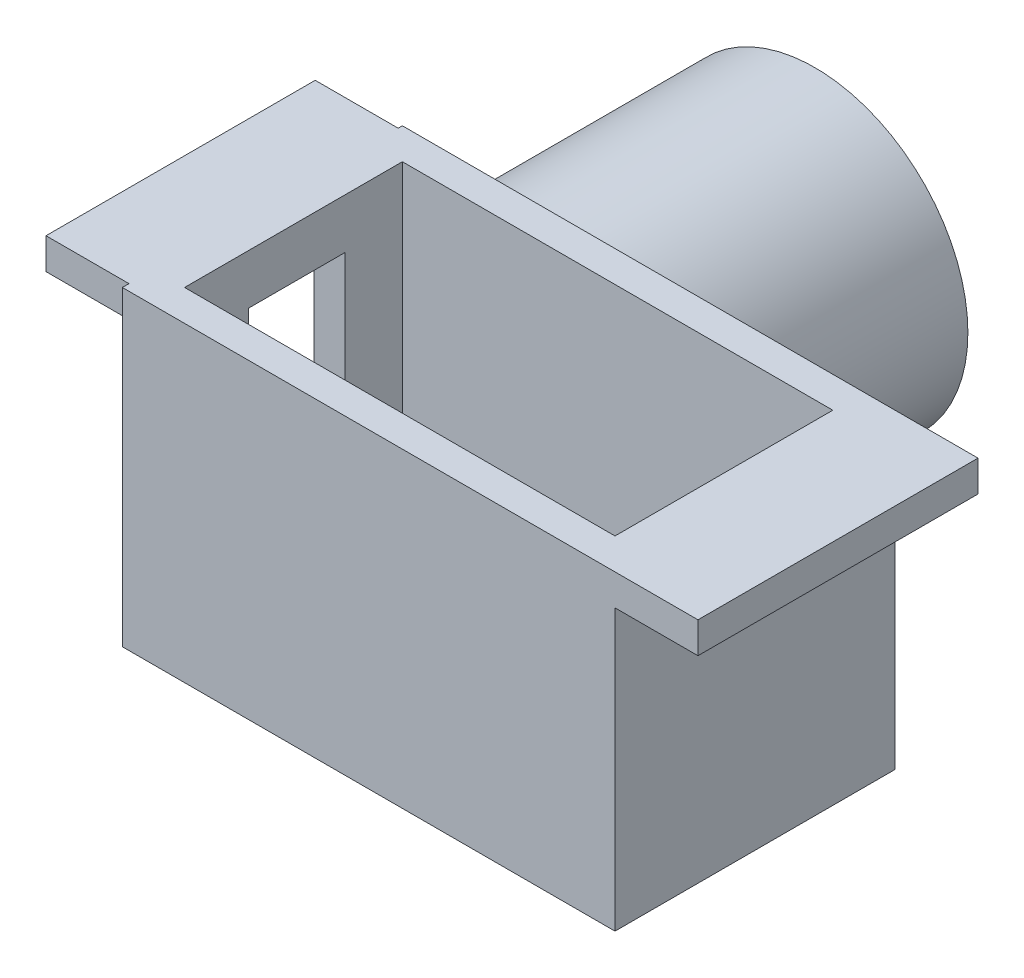
SolidWorks part; units mm, degrees
ref_plane "Front Plane" through (0, 0, 0) normal (0, 0, 1) x (1, 0, 0)
ref_plane "Top Plane" through (0, 0, 0) normal (0, 1, 0) x (1, 0, 0)
ref_plane "Right Plane" through (0, 0, 0) normal (1, 0, 0) x (0, 0, -1)
sketch "Sketch1" plane through (0, 0, 0) normal (0, 1, 0) x (1, 0, 0)
  line L0 (10.9993, 19.4492) -> (58.4993, 19.4492)
  line L5 (13.9993, 16.4492) -> (55.4993, 16.4492)
  line L6 (13.9993, 16.4492) -> (13.9993, -4.5508)
  line L7 (13.9993, -4.5508) -> (55.4993, -4.5508)
  line L8 (55.4993, 16.4492) -> (55.4993, -4.5508)
  line L9 (58.4993, 19.4492) -> (58.4993, -7.5508)
  line L10 (10.9993, -7.5508) -> (58.4993, -7.5508)
  line L11 (10.9993, 19.4492) -> (10.9993, -7.5508)
  dimension "D1" = 41.5
  dimension "D2" = 21
  dimension "D3" = 3
extrude "Boss-Extrude2" add sketch "Sketch1" against normal blind 30 contours L8 L5 L6 L7 | L0 L9 L10 L11
sketch "Sketch2" plane through (10.9993, 0, 0) normal (-1, 0, 0) x (0, 0, 1)
  line L1 (-10.9136, -4.8151) -> (-1.6054, -4.8151)
  line L2 (-10.9136, -4.8151) -> (-10.9136, -28.1888)
  line L3 (-10.9136, -28.1888) -> (-1.6054, -28.1888)
  line L4 (-1.6054, -4.8151) -> (-1.6054, -28.1888)
extrude "Cut-Extrude1" cut sketch "Sketch2" against normal blind 30
sketch "Sketch3" plane through (10.9993, 0, 0) normal (-1, 0, 0) x (0, 0, 1)
  line L0 (-19.4492, 0) -> (7.5508, 0) construction
  line L1 (-19.0456, 0) -> (6.9112, 0)
  line L2 (-19.0456, 0) -> (-19.0456, -3)
  line L3 (-19.0456, -3) -> (6.9112, -3)
  line L4 (6.9112, 0) -> (6.9112, -3)
  dimension "D1" = 3
extrude "Boss-Extrude3" add sketch "Sketch3" along normal blind 8
sketch "Sketch4" plane through (58.4993, 0, 0) normal (1, 0, 0) x (0, 0, -1)
  line L0 (19.4492, -30) -> (19.4492, 0) construction
  line L1 (-7.5508, 0) -> (19.4492, 0)
  line L2 (-7.5508, 0) -> (-7.5508, -3)
  line L3 (-7.5508, -3) -> (19.4492, -3)
  line L4 (19.4492, 0) -> (19.4492, -3)
  dimension "D1" = 3
extrude "Boss-Extrude4" add sketch "Sketch4" along normal blind 8
sketch "Sketch5" plane through (0, 0, -19.4492) normal (0, 0, -1) x (-1, 0, 0)
  line L0 (-10.9993, -17.3157) -> (-10.9993, -15)
  line L1 (-10.9993, -30) -> (-10.9993, 0) construction
  line L2 (-10.9993, -15) -> (-15.5481, -15)
  line L3 (-10.9993, -15) -> (-58.4993, -15) construction
  line L4 (-58.4993, -30) -> (-58.4993, -3) construction
  line L5 (-25.7759, -15) -> (-25.7759, 0) construction
  line L6 (-10.9993, 0) -> (-66.4993, 0) construction
  line L7 (-25.7759, 0) -> (-25.7759, -30) construction
  line L8 (-10.9993, -30) -> (-58.4993, -30) construction
  circle A0 centre (-25.7759, -15) radius 12.75
  circle A1 centre (-25.7759, -15) radius 14.75
  dimension "D1" = 25.5
  dimension "D2" = 2
extrude "Boss-Extrude5" add sketch "Sketch5" along normal blind 25
